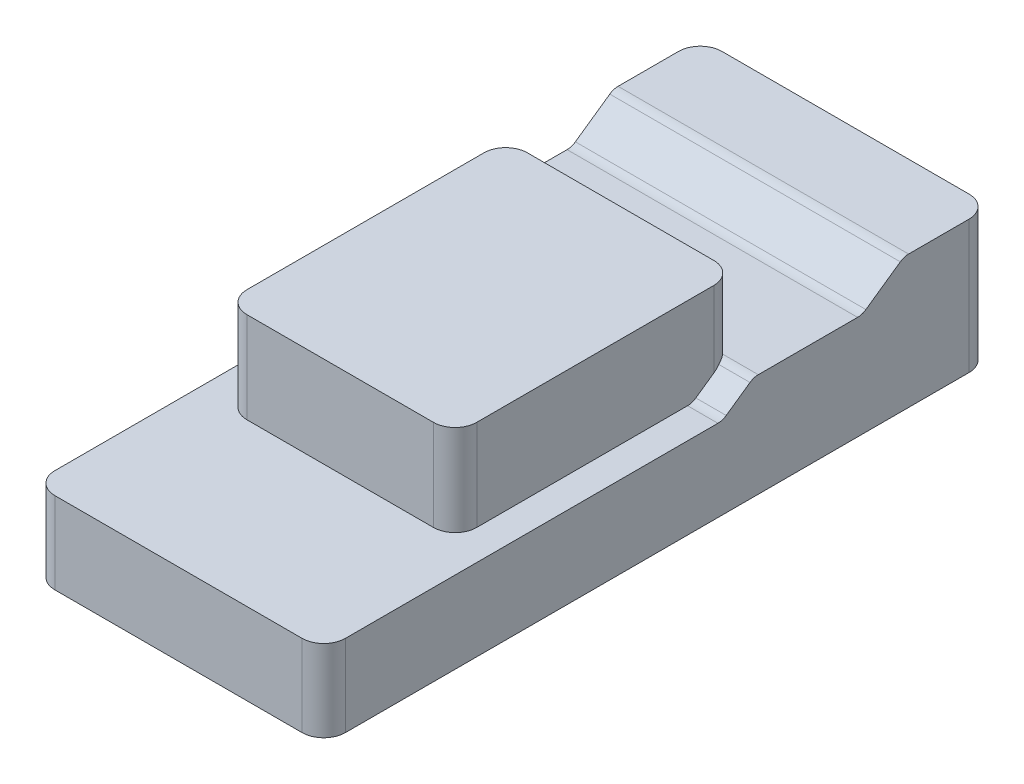
SolidWorks part; units mm, degrees
ref_plane "Front Plane" through (0, 0, 0) normal (0, 0, 1) x (1, 0, 0)
ref_plane "Top Plane" through (0, 0, 0) normal (0, 1, 0) x (1, 0, 0)
ref_plane "Right Plane" through (0, 0, 0) normal (1, 0, 0) x (0, 0, -1)
sketch "Sketch1" plane through (0, 0, 0) normal (1, 0, 0) x (0, 0, -1)
  line L0 (46.15, 0) -> (-46.15, 0)
  line L1 (-46.15, 0) -> (-46.15, 11.3)
  line L2 (46.15, 0) -> (46.15, 18.39)
  line L3 (46.15, 18.39) -> (34.15, 18.39)
  line L4 (0, 0) -> (0, 14.33) construction
  line L5 (34.15, 18.39) -> (28.3517, 14.33)
  line L6 (28.3517, 14.33) -> (13.3517, 14.33)
  line L7 (13.3517, 14.33) -> (9.0244, 11.3)
  line L8 (9.0244, 11.3) -> (-46.15, 11.3)
  point P4 (0, 0)
  dimension "D1" = 92.3
  dimension "D2" = 11.3
  dimension "D3" = 18.39
  dimension "D4" = 12
  dimension "D5" = 14.33
  dimension "D6" = 35
  dimension "D7" = 35
  dimension "D8" = 15
extrude "Boss-Extrude1" add sketch "Sketch1" against normal blind 40.2
sketch "Sketch2" plane through (0, 11.3, 0) normal (0, 1, 0) x (1, 0, 0)
  line L0 (-20.1, 9.0244) -> (-20.1, 15.0244) construction
  line L1 (-40.2, 9.0244) -> (0, 9.0244) construction
  line L2 (-4.2, 15.0244) -> (-36, 15.0244)
  line L3 (-36, 15.0244) -> (-36, -23.7756)
  line L4 (-36, -23.7756) -> (-4.2, -23.7756)
  line L5 (-4.2, -23.7756) -> (-4.2, 15.0244)
  point P7 (-20.1, 15.0244)
  dimension "D1" = 6
  dimension "D2" = 31.8
  dimension "D3" = 38.8
extrude "Boss-Extrude2" add sketch "Sketch2" along normal blind 12.6
fillet "Fillet1" radius 3 4 edges at (-36, 19.115, -15.0244) (-4.2, 19.115, -15.0244) (-36, 17.6, 23.7756) (-4.2, 17.6, 23.7756)
fillet "Fillet2" radius 3 4 edges at (-40.2, 9.195, -46.15) (0, 9.195, -46.15) (-40.2, 5.65, 46.15) (0, 5.65, 46.15)
fillet "Fillet3" radius 2 6 edges at (-38.1, 11.3, -9.0244) (-2.1, 11.3, -9.0244) (-37.9452, 14.33, -13.3517) (-2.2548, 14.33, -13.3517) (-20.1, 14.33, -28.3517) (-20.1, 18.39, -34.15)
sketch "Sketch3" plane through (0, 23.9, 0) normal (0, 1, 0) x (1, 0, 0)
  line L0 (-30.2375, 45.5948) -> (72.4292, 45.5948) construction
  line L1 (-9.6219, 70.8632) -> (93.0448, 70.8632) construction
sketch "Sketch4" plane through (0, 11.3, 0) normal (0, 1, 0) x (1, 0, 0)
  line L0 (-156.5718, 11.1899) -> (-33.2384, 11.1899) construction
sketch "Sketch5" plane through (0, 14.33, 0) normal (0, 1, 0) x (1, 0, 0)
  line L0 (-151.8506, 1.7922) -> (-31.184, 1.7922) construction
sketch "Sketch6" plane through (0, 18.39, 0) normal (0, 1, 0) x (1, 0, 0)
  line L0 (-155.8256, 61.6473) -> (-32.4923, 61.6473) construction
